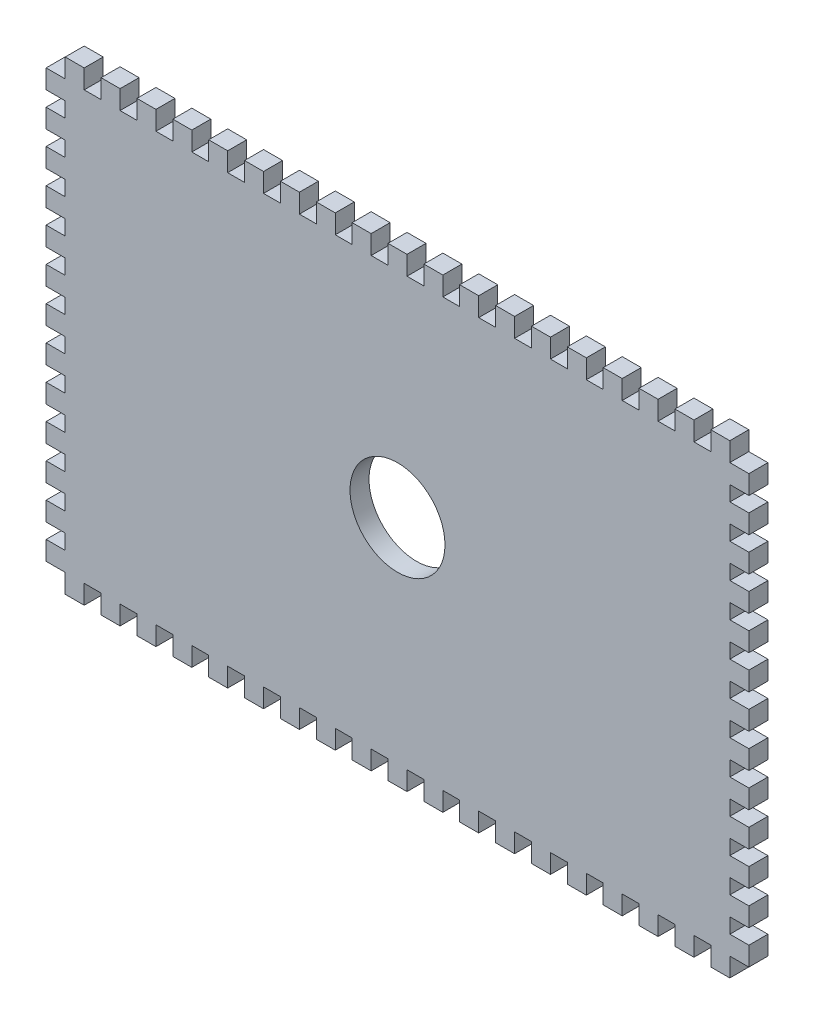
SolidWorks part; units mm, degrees
ref_plane "Plano frontal" through (0, 0, 0) normal (0, 0, 1) x (1, 0, 0)
ref_plane "Plano superior" through (0, 0, 0) normal (0, 1, 0) x (1, 0, 0)
ref_plane "Plano direito" through (0, 0, 0) normal (1, 0, 0) x (0, 0, -1)
sketch "Esboço1" plane through (0, 0, 0) normal (0, 0, 1) x (1, 0, 0)
  line L0 (-110, 0) -> (110, 0) construction
  line L13 (0, 0) -> (0, 67.5) construction
  line L14 (0, 0) -> (-105, 0) construction
  line L15 (-105, -67.5) -> (-105, 67.5)
  line L16 (0, 0) -> (105, 0) construction
  line L17 (105, -67.5) -> (105, 67.5)
  line L18 (-105, 67.5) -> (-2.5, 67.5)
  line L19 (-105, -67.5) -> (105, -67.5)
  line L20 (-2.5, 67.5) -> (2.5, 67.5)
  line L23 (2.5, 67.5) -> (105, 67.5)
  point P0 (0, 0)
  point P6 (0, 0)
  point P8 (110, 0)
  point P10 (0, 72.5)
  point P17 (-105, 0)
  point P21 (105, 0)
  point P23 (0, 67.5)
  point P26 (0, 67.5)
  dimension "D1" = 210
  dimension "D3" = 135
  dimension "D5" = 5
extrude "Ressalto-extrusão9" add sketch "Esboço1" along normal blind 6 separate body
sketch "Esboço2" plane through (0, 0, 6) normal (0, 0, 1) x (1, 0, 0)
  line L0 (0, 0) -> (0, 67.5) construction
  line L1 (105, 67.5) -> (-105, 67.5) construction
  line L2 (-3, 67.5) -> (3, 67.5)
  line L3 (-3, 67.5) -> (-3, 73.5)
  line L4 (-3, 73.5) -> (3, 73.5)
  line L5 (3, 73.5) -> (3, 67.5)
  line L6 (0, 0) -> (0, -67.5) construction
  line L7 (-105, -67.5) -> (105, -67.5) construction
  line L8 (-3, -67.5) -> (3, -67.5)
  line L9 (-3, -67.5) -> (-3, -73.5)
  line L10 (-3, -73.5) -> (3, -73.5)
  line L11 (3, -73.5) -> (3, -67.5)
  point P8 (0, 67.5)
  point P15 (0, -67.5)
  dimension "D3" = 6
  dimension "D1" = 6
  dimension "D2" = 6
extrude "Ressalto-extrusão10" add sketch "Esboço2" against normal blind 6
pattern_linear "Padrão linear1" count 10 spacing 11.33 along (-1, 0, 0) count 10 spacing 11.33 along (1, 0, 0) of "Ressalto-extrusão10"
sketch "Esboço3" plane through (0, 0, 6) normal (0, 0, 1) x (1, 0, 0)
  circle A0 centre (0, 0) radius 15
  dimension "D1" = 30
extrude "Corte-extrusão1" cut sketch "Esboço3" against normal blind 10
sketch "Esboço4" plane through (0, 0, 6) normal (0, 0, 1) x (1, 0, 0)
  line L0 (0, 0) -> (-105, 0) construction
  line L1 (-105, 67.5) -> (-105, -67.5) construction
  line L2 (0, 0) -> (105, 0) construction
  line L3 (105, -67.5) -> (105, 67.5) construction
  line L4 (-105, -3) -> (-105, 3)
  line L5 (-105, 3) -> (-111, 3)
  line L6 (-111, 3) -> (-111, -3)
  line L7 (-111, -3) -> (-105, -3)
  line L8 (105, -3) -> (105, 3)
  line L9 (105, -3) -> (111, -3)
  line L10 (111, -3) -> (111, 3)
  line L11 (111, 3) -> (105, 3)
  point P11 (-105, 0)
  point P16 (105, 0)
  dimension "D1" = 6
  dimension "D2" = 6
  dimension "D3" = 6
extrude "Ressalto-extrusão11" add sketch "Esboço4" against normal blind 6
pattern_linear "Padrão linear2" count 7 spacing 10.75 along (0, 1, 0) count 7 spacing 10.75 along (0, -1, 0) of "Ressalto-extrusão11"
